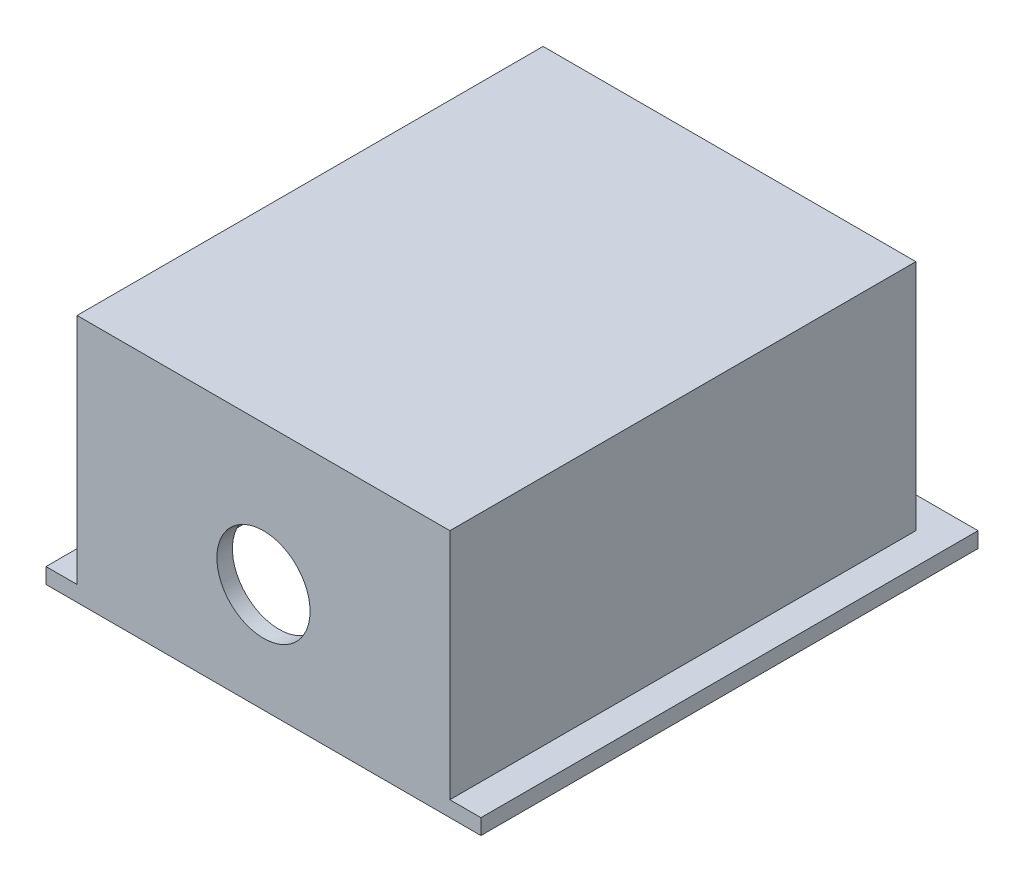
SolidWorks part; units mm, degrees
ref_plane "前视基准面" through (0, 0, 0) normal (0, 0, 1) x (1, 0, 0)
ref_plane "上视基准面" through (0, 0, 0) normal (0, 1, 0) x (1, 0, 0)
ref_plane "右视基准面" through (0, 0, 0) normal (1, 0, 0) x (0, 0, -1)
sketch "草图1" plane through (0, 0, 0) normal (0, 0, 1) x (1, 0, 0)
  line L1 (-60, 40) -> (60, 40)
  line L2 (-60, 40) -> (-60, -40)
  line L3 (-60, -40) -> (60, -40)
  line L4 (60, 40) -> (60, -40)
  line L5 (0, -40) -> (0, 40) construction
  line L6 (-60, 0) -> (60, 0) construction
  point P0 (0, 0)
  dimension "D1" = 120
  dimension "D2" = 80
extrude "凸台-拉伸1" add sketch "草图1" along normal blind 150
shell "抽壳1" thickness 5
sketch "草图2" plane through (0, -40, 0) normal (0, -1, 0) x (1, 0, 0)
  line L0 (-60, 150) -> (-60, 0) construction
  line L2 (-70, 150) -> (-70, -10)
  line L3 (-70, -10) -> (70, -10)
  line L4 (70, 150) -> (70, -10)
  line L5 (-60, 0) -> (60, 0) construction
  line L6 (-60, 150) -> (-70, 150)
  line L7 (-60, 150) -> (70, 150)
  line L14 (-60, 150) -> (60, 150)
  line L15 (-60, 150) -> (-60, 0)
  line L16 (-60, 0) -> (60, 0)
  line L17 (60, 150) -> (60, 0)
  point P4 (0, -10)
  point P8 (-60, 75)
  line M11 (-60, 0) -> (60, 0)
  line M12 (60, 0) -> (60, 150)
  line M14 (-60, 150) -> (-60, 0)
  dimension "D1" = 10
  dimension "D2" = 10
extrude "凸台-拉伸2" add sketch "草图2" against normal blind 5 contours L7 L6 L2 L3 L4 M12 M11 M14
sketch "草图3" plane through (0, 0, 0) normal (0, 0, -1) x (-1, 0, 0)
  line L0 (70, -40) -> (-70, -40) construction
  circle A0 centre (0, -5) radius 15
  dimension "D1" = 30
  dimension "D2" = 35
extrude "切除-拉伸1" cut sketch "草图3" against normal blind 10000
